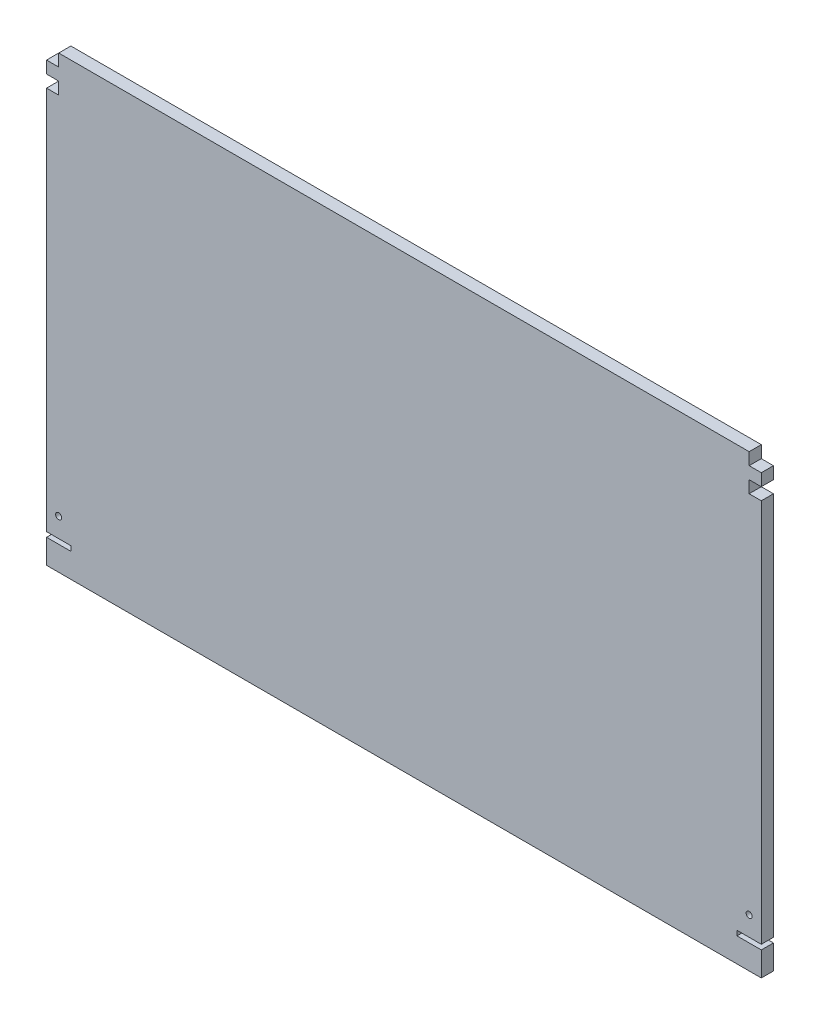
SolidWorks part; units mm, degrees
ref_plane "Front Plane" through (0, 0, 0) normal (0, 0, 1) x (1, 0, 0)
ref_plane "Top Plane" through (0, 0, 0) normal (0, 1, 0) x (1, 0, 0)
ref_plane "Right Plane" through (0, 0, 0) normal (1, 0, 0) x (0, 0, -1)
sketch "Sketch1" plane through (0, 0, 0) normal (0, 0, 1) x (1, 0, 0)
  line L0 (-147, 0) -> (-147, 47.9667) construction
  line L1 (0, 0) -> (-294, 0)
  line L2 (0, 0) -> (0, -185)
  line L3 (0, -185) -> (-294, -185)
  line L4 (-294, 0) -> (-294, -185)
  line L6 (0, 0) -> (0, -5)
  line L7 (0, -5) -> (-5, -5)
  line L8 (-5, 0) -> (-5, -5)
  line L9 (0, -10) -> (-5, -10)
  line L10 (0, -10) -> (0, -15)
  line L11 (0, -15) -> (-5, -15)
  line L12 (-5, -10) -> (-5, -15)
  line L13 (-289, -10) -> (-289, -15)
  line L14 (-294, -15) -> (-289, -15)
  line L15 (-294, -10) -> (-294, -15)
  line L16 (-294, -10) -> (-289, -10)
  line L17 (-289, 0) -> (-289, -5)
  line L18 (-294, -5) -> (-289, -5)
  line L19 (-294, 0) -> (-294, -5)
  dimension "D1" = 185
  dimension "D2" = 294
  dimension "D3" = 5
  dimension "D4" = 5
  dimension "D5" = 5
  dimension "D6" = 5
  dimension "D7" = 5
  dimension "D8" = 180
extrude "Boss-Extrude1" add sketch "Sketch1" along normal blind 5
sketch "Sketch2" plane through (0, 0, 0) normal (0, 0, -1) x (-1, 0, 0)
  line L0 (294, -15) -> (294, -185) construction
  line L1 (294, -175) -> (284, -175)
  line L2 (294, -175) -> (294, -173)
  line L3 (294, -173) -> (284, -173)
  line L4 (284, -175) -> (284, -173)
  line L5 (0, -185) -> (294, -185) construction
  line L6 (147, -185) -> (147, -117.0334) construction
  line L7 (10, -175) -> (10, -173)
  line L8 (0, -173) -> (10, -173)
  line L9 (0, -175) -> (0, -173)
  line L10 (0, -175) -> (10, -175)
  dimension "D1" = 2
  dimension "D2" = 10
  dimension "D3" = 10
extrude "Cut-Extrude1" cut sketch "Sketch2" against normal blind 5
sketch "Sketch3" plane through (0, 0, 0) normal (0, 0, -1) x (-1, 0, 0)
  line L0 (0, -185) -> (294, -185) construction
  line L1 (294, -175) -> (294, -185) construction
  line L2 (147, -185) -> (147, -131.8636) construction
  circle A0 centre (289, -165) radius 1.25
  circle A1 centre (5, -165) radius 1.25
  dimension "D2" = 5
  dimension "D3" = 2.5
  dimension "D1" = 20
extrude "Cut-Extrude2" cut sketch "Sketch3" against normal blind 5
